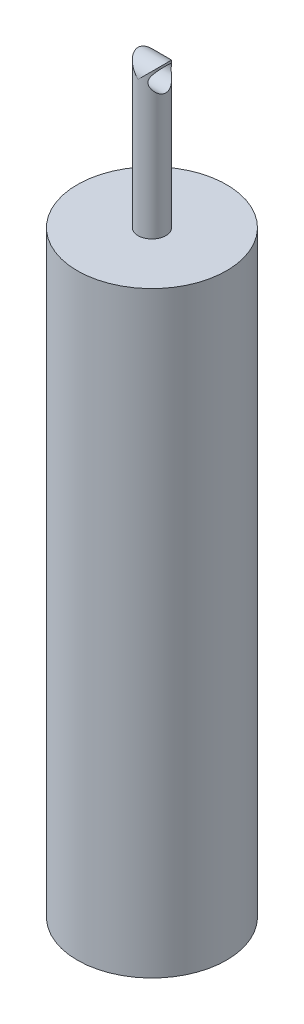
SolidWorks part; units mm, degrees
ref_plane "Front Plane" through (0, 0, 0) normal (0, 0, 1) x (1, 0, 0)
ref_plane "Top Plane" through (0, 0, 0) normal (0, 1, 0) x (1, 0, 0)
ref_plane "Right Plane" through (0, 0, 0) normal (1, 0, 0) x (0, 0, -1)
sketch "Sketch1" plane through (0, 0, 0) normal (0, 1, 0) x (1, 0, 0)
  circle A0 centre (0, 0) radius 25.4
  dimension "D1" = 50.8
extrude "Boss-Extrude1" add sketch "Sketch1" along normal blind 203.2
sketch "Sketch2" plane through (0, 203.2, 0) normal (0, 1, 0) x (1, 0, 0)
  circle A0 centre (0, 0) radius 4.7308
  dimension "D1" = 9.4615
extrude "Boss-Extrude2" add sketch "Sketch2" along normal blind 50.8
sketch "Sketch3" plane through (0, 0, 0) normal (1, 0, 0) x (0, 0, -1)
  line L0 (4.7308, 203.2) -> (4.7308, 254) construction
  line L2 (4.7308, 254) -> (-4.7308, 254) construction
  line L3 (-4.7308, 254) -> (-4.7308, 203.2) construction
  line L6 (-4.7308, 244.5385) -> (4.7308, 244.5385)
  line L7 (-4.7308, 244.5385) -> (-4.7308, 254)
  line L8 (-4.7308, 254) -> (4.7308, 254)
  line L9 (4.7308, 244.5385) -> (4.7308, 254)
  line L10 (-4.7308, 244.5385) -> (4.7308, 254) construction
  line L11 (-4.7308, 254) -> (4.7308, 244.5385) construction
  circle A0 centre (0, 249.2692) radius 4.7308
  circle A1 centre (0, 249.2692) radius 3.9688
  dimension "D1" = 7.9375
extrude "Cut-Extrude1" cut sketch "Sketch3" against normal through all both and the other way through all contours A1 | A0 L8 L7 | A0 L9 L8
